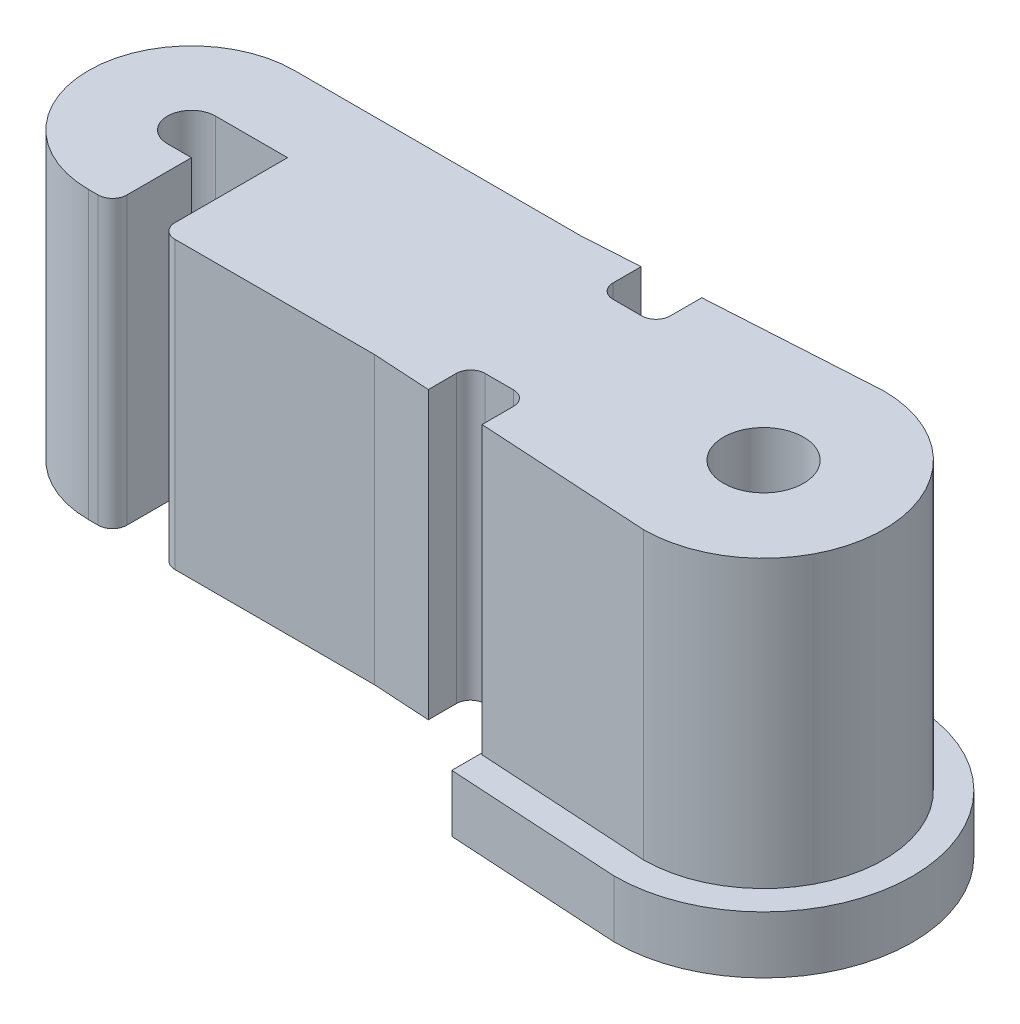
SolidWorks part; units mm, degrees
ref_plane "Front Plane" through (0, 0, 0) normal (0, 0, 1) x (1, 0, 0)
ref_plane "Top Plane" through (0, 0, 0) normal (0, 1, 0) x (1, 0, 0)
ref_plane "Right Plane" through (0, 0, 0) normal (1, 0, 0) x (0, 0, -1)
sketch "Sketch3" plane through (0, 0, 0) normal (0, 1, 0) x (1, 0, 0)
  line L0 (-5, 0.75) -> (0, 1.05) construction
  line L3 (0, -1.05) -> (-5, -0.75) construction
  line L4 (-2.5, 0.9) -> (-2, 0.93)
  line L6 (-4.25, 0) -> (-5.75, 0) construction
  line L7 (-2, 0.93) -> (-2, 0.56)
  line L8 (-2.5, 0.9) -> (-5, 0.9)
  line L9 (-2.5, 0.9) -> (-2.5, -0.9) construction
  line L10 (-2.5, -0.9) -> (-5, -0.9)
  line L11 (-5, 0.9) -> (-5, -0.9) construction
  line L12 (-2, 0.96) -> (-1.5, 0.96) construction
  line L13 (-2, 0.96) -> (-2, 0.56) construction
  line L14 (-2, 0.56) -> (-1.5, 0.56)
  line L15 (-1.5, 0.96) -> (-1.5, 0.56)
  line L16 (-1.5, -0.56) -> (-2, -0.56)
  line L17 (-1.5, -0.56) -> (-1.5, -0.96)
  line L18 (-1.5, -0.96) -> (-2, -0.96) construction
  line L19 (-2, -0.56) -> (-2, -0.96) construction
  line L21 (-2.5, -0.9) -> (-2, -0.93)
  line L22 (-2, -0.93) -> (-2, -0.56)
  line L23 (-1.5, 0.96) -> (0, 1.05)
  line L24 (0, -1.05) -> (-1.5, -0.96)
  circle A2 centre (0, 0) radius 0.6 construction
  circle A3 centre (0, 0) radius 0.4 construction
  circle A4 centre (-5, 0) radius 0.35 construction
  circle A5 centre (0, 0) radius 1.05 construction
  circle A6 centre (-5, 0) radius 0.75 construction
  arc A7 (-5, 0.9) -> (-5, -0.9) centre (-5, 0) ccw
  arc A8 (0, 1.05) -> (0, -1.05) centre (0, 0) cw
  point P4 (-2, -0.93)
  point P15 (-5, 0)
  point P16 (-2, 0.93)
  point P22 (-5, 0)
  dimension "D2" = 1.2
  dimension "D3" = 0.8
  dimension "D4" = 0.7
  dimension "D6" = 5
  dimension "D1" = 1.5
  dimension "D5" = 2.1
  dimension "D7" = 0.4
  dimension "D9" = 2.5
  dimension "D10" = 1.8
  dimension "D11" = 2.5
  dimension "D12" = 0.5
  dimension "D14" = 1.5
extrude "Boss-Extrude1" add sketch "Sketch3" along normal blind 2.5 contours L8 A7 L10 L21 L22 L16 L17 L24 A8 L23 L15 L14 L7 L4
sketch "Sketch4" plane through (0, 2.5, 0) normal (0, 1, 0) x (1, 0, 0)
  line L3 (-4.79, -0.9) -> (-4.37, -0.9)
  line L5 (-4.79, -0.9) -> (-4.79, -0.21)
  line L6 (-4.37, -0.9) -> (-4.37, 0.21)
  line L7 (-4.37, 0.21) -> (-5, 0.21)
  line L8 (-4.79, -0.21) -> (-5, -0.21)
  line L9 (-2.5, -0.9) -> (-5, -0.9) construction
  circle A0 centre (0, 0) radius 0.35
  circle A1 centre (-5, 0) radius 0.375 construction
  circle A2 centre (-5, 0) radius 0.21 construction
  arc A3 (-5, 0.21) -> (-5, -0.21) centre (-5, 0) ccw
  point P7 (0, 0)
  point P9 (0, 0)
  point P11 (-4.79, -0.21)
  dimension "D1" = 0.7
  dimension "D2" = 0.75
  dimension "D4" = 0.42
  dimension "D3" = 0.42
extrude "Through Holes" cut sketch "Sketch4" against normal through all
fillet "Fillet1" radius 0.125 6 edges at (-2, 1.25, 0.56) (-1.5, 1.25, 0.56) (-1.5, 1.25, -0.56) (-2, 1.25, -0.56) (-4.37, 1.25, 0.9) (-4.79, 1.25, 0.9)
sketch "Sketch5" plane through (0, 0, 0) normal (0, 1, 0) x (1, 0, 0)
  line L2 (-1.515, -1.2096) -> (-1.515, 1.2096)
  line L4 (-1.515, 1.2096) -> (-0.0079, 1.3)
  line L5 (-0.0079, -1.3) -> (-1.515, -1.2096)
  line L6 (-1.515, 1.2096) -> (-0.0079, 1.3)
  line L7 (-0.0079, -1.3) -> (-1.515, -1.2096)
  circle A1 centre (0, 0) radius 0.125
  arc A2 (-0.0079, -1.3) -> (-0.0079, 1.3) centre (0, 0) ccw
  arc A3 (-0.0079, -1.3) -> (-0.0079, 1.3) centre (0, 0) ccw
  dimension "D2" = 0.25
  dimension "D1" = 0.25
extrude "Boss-Extrude2" add sketch "Sketch5" against normal blind 0.5
